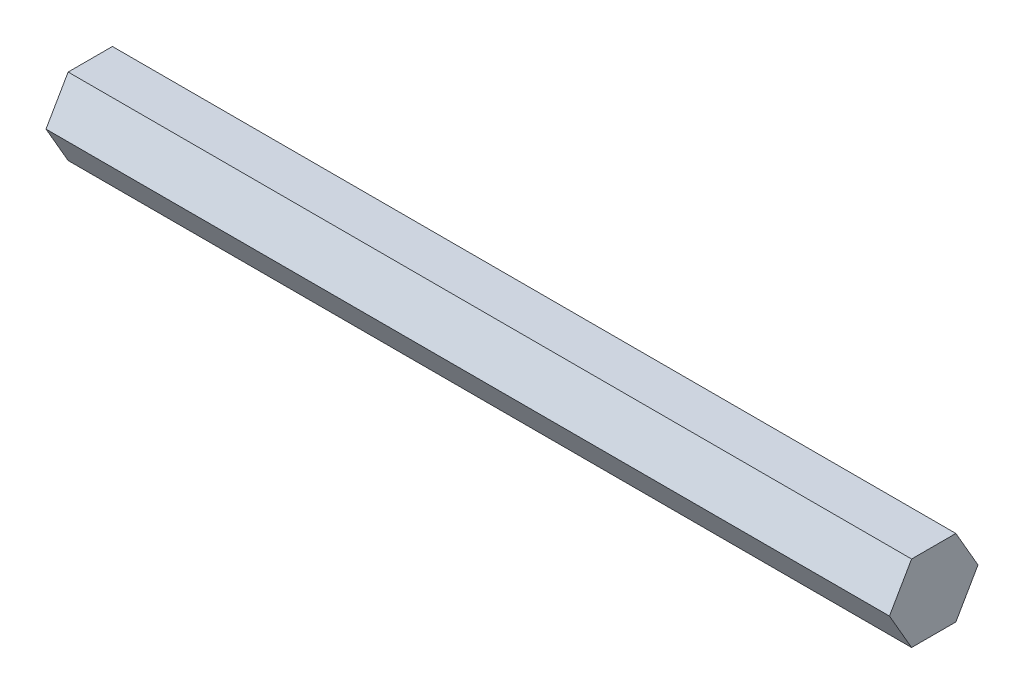
SolidWorks part; units mm, degrees
material "6061 Alloy"
ref_plane "Front Plane" through (0, 0, 0) normal (0, 0, 1) x (1, 0, 0)
ref_plane "Top Plane" through (0, 0, 0) normal (0, 1, 0) x (1, 0, 0)
ref_plane "Right Plane" through (0, 0, 0) normal (1, 0, 0) x (0, 0, -1)
sketch "Sketch1" [suppressed] plane through (0, 0, 0) normal (1, 0, 0) x (0, 0, -1)
  line L1 (7.3323, 0) -> (3.6662, 6.35)
  line L2 (3.6662, 6.35) -> (-3.6662, 6.35)
  line L3 (-3.6662, 6.35) -> (-7.3323, 0)
  line L4 (-7.3323, 0) -> (-3.6662, -6.35)
  line L5 (-3.6662, -6.35) -> (3.6662, -6.35)
  line L6 (3.6662, -6.35) -> (7.3323, 0)
  circle A0 centre (0, 0) radius 6.35 construction
  dimension "D1" = 12.7
extrude "Boss-Extrude1" [suppressed] add sketch "Sketch1" along normal mid plane 152.4
sketch "Sketch2" [suppressed] plane through (76.2, 0, 0) normal (1, 0, 0) x (0, 0, -1)
  circle A0 centre (0, 0) radius 3.1115
  dimension "D1" = 6.223
extrude "Cut-Extrude1" [suppressed] cut sketch "Sketch2" against normal blind 25.4 flip side to cut
sketch "Sketch3" plane through (0, 0, 0) normal (1, 0, 0) x (0, 0, -1)
  line L1 (7.3323, 0) -> (3.6662, 6.35)
  line L2 (3.6662, 6.35) -> (-3.6662, 6.35)
  line L3 (-3.6662, 6.35) -> (-7.3323, 0)
  line L4 (-7.3323, 0) -> (-3.6662, -6.35)
  line L5 (-3.6662, -6.35) -> (3.6662, -6.35)
  line L6 (3.6662, -6.35) -> (7.3323, 0)
  circle A0 centre (0, 0) radius 6.35 construction
  dimension "D1" = 12.7
extrude "Boss-Extrude2" add sketch "Sketch3" along normal mid plane 139.7
